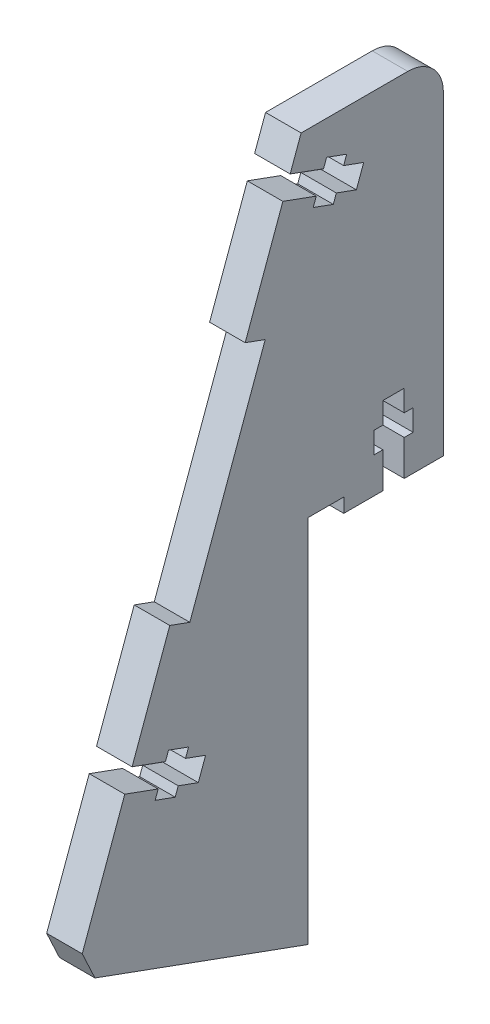
SolidWorks part; units mm, degrees
material "Maple"
ref_plane "Front Plane" through (0, 0, 0) normal (0, 0, 1) x (1, 0, 0)
ref_plane "Top Plane" through (0, 0, 0) normal (0, 1, 0) x (1, 0, 0)
ref_plane "Right Plane" through (0, 0, 0) normal (1, 0, 0) x (0, 0, -1)
sketch "Sketch1" plane through (0, 0, 0) normal (1, 0, 0) x (0, 0, -1)
  line L0 (0, 0) -> (-14, 0)
  line L1 (-14, 0) -> (-14, 2)
  line L2 (-14, 2) -> (-19, 2)
  line L3 (-19, 2) -> (-19, -50)
  line L4 (-19, -50) -> (-51.8079, -38.0589)
  line L5 (-51.8079, -38.0589) -> (-20, 49.3325)
  line L6 (-20, 49.3325) -> (0, 49.3325)
  line L7 (0, 49.3325) -> (0, 0)
  line L8 (-22.0521, 43.6943) -> (-17.5507, 42.056) construction
  line L9 (-44.2834, -17.3857) -> (-36.2862, -20.2964) construction
  dimension "D1" = 5
  dimension "D2" = 2
  dimension "D3" = 14
  dimension "D4" = 65
  dimension "D5" = 6
  dimension "D6" = 22
  dimension "D7" = 50
  dimension "D8" = 20
  dimension "D9" = 20
extrude "Boss-Extrude1" add sketch "Sketch1" along normal blind 5
sketch "Sketch2" plane through (5, 0, 0) normal (1, 0, 0) x (0, 0, -1)
  line L0 (-21.5391, 45.1039) -> (-16.8406, 43.3938)
  line L1 (-20, 49.3325) -> (-51.8079, -38.0589) construction
  line L2 (-16.8406, 43.3938) -> (-16.4131, 44.5684)
  line L3 (-16.4131, 44.5684) -> (-13.594, 43.5423)
  line L4 (-13.594, 43.5423) -> (-14.0215, 42.3677)
  line L5 (-14.0215, 42.3677) -> (-11.2025, 41.3417)
  line L6 (-11.2025, 41.3417) -> (-12.2285, 38.5226)
  line L7 (-12.2285, 38.5226) -> (-15.0476, 39.5486)
  line L8 (-15.0476, 39.5486) -> (-15.4751, 38.374)
  line L9 (-15.4751, 38.374) -> (-18.2942, 39.4001)
  line L10 (-18.2942, 39.4001) -> (-17.8667, 40.5747)
  line L11 (-17.8667, 40.5747) -> (-22.5652, 42.2848)
  line L12 (-51.8079, -38.0589) -> (-20, 49.3325) construction
  line L13 (-22.5652, 42.2848) -> (-21.5391, 45.1039)
  line L14 (-44.2834, -17.3857) -> (-22.0521, 43.6943) construction
  line L15 (-33.1678, 13.1543) -> (-15.5503, 6.7421) construction
  line L16 (-43.7704, -15.9761) -> (-44.7965, -18.7952)
  line L17 (-39.0719, -17.6862) -> (-43.7704, -15.9761)
  line L18 (-38.6444, -16.5116) -> (-39.0719, -17.6862)
  line L19 (-35.8253, -17.5377) -> (-38.6444, -16.5116)
  line L20 (-36.2529, -18.7123) -> (-35.8253, -17.5377)
  line L21 (-33.4338, -19.7384) -> (-36.2529, -18.7123)
  line L22 (-34.4598, -22.5574) -> (-33.4338, -19.7384)
  line L23 (-37.2789, -21.5314) -> (-34.4598, -22.5574)
  line L24 (-37.7064, -22.706) -> (-37.2789, -21.5314)
  line L25 (-40.5255, -21.6799) -> (-37.7064, -22.706)
  line L26 (-40.098, -20.5053) -> (-40.5255, -21.6799)
  line L27 (-44.7965, -18.7952) -> (-40.098, -20.5053)
  line L28 (-27.8665, 27.7196) -> (-38.4691, -1.4109)
  line L29 (-38.4691, -1.4109) -> (-35.65, -2.437)
  line L30 (-35.65, -2.437) -> (-25.0474, 26.6935)
  line L31 (-25.0474, 26.6935) -> (-27.8665, 27.7196)
  line L32 (-8.5, 0) -> (-8.5, 5)
  line L33 (0, 0) -> (-14, 0) construction
  line L34 (-8.5, 5) -> (-9.75, 5)
  line L35 (-9.75, 5) -> (-9.75, 8)
  line L36 (-9.75, 8) -> (-8.5, 8)
  line L37 (-8.5, 8) -> (-8.5, 11)
  line L38 (-8.5, 11) -> (-5.5, 11)
  line L39 (-5.5, 11) -> (-5.5, 8)
  line L40 (-5.5, 8) -> (-4.25, 8)
  line L41 (-4.25, 8) -> (-4.25, 5)
  line L42 (-4.25, 5) -> (-5.5, 5)
  line L43 (-5.5, 5) -> (-5.5, 0)
  line L44 (-5.5, 0) -> (-8.5, 0)
  point P17 (-22.0521, 43.6943)
  point P53 (-7, 0)
  dimension "D1" = 3
  dimension "D2" = 11
  dimension "D3" = 5
  dimension "D4" = 3
  dimension "D5" = 5.5
  dimension "D6" = 17
  dimension "D7" = 17
  dimension "D8" = 3
  dimension "D9" = 5
extrude "Cut-Extrude1" cut sketch "Sketch2" against normal through all
chamfer "Chamfer1" distance 3 angle 45 1 edges at (2.5, -38.0589, 51.8079)
fillet "Fillet1" radius 5 1 edges at (2.5, 49.3325, 0)
